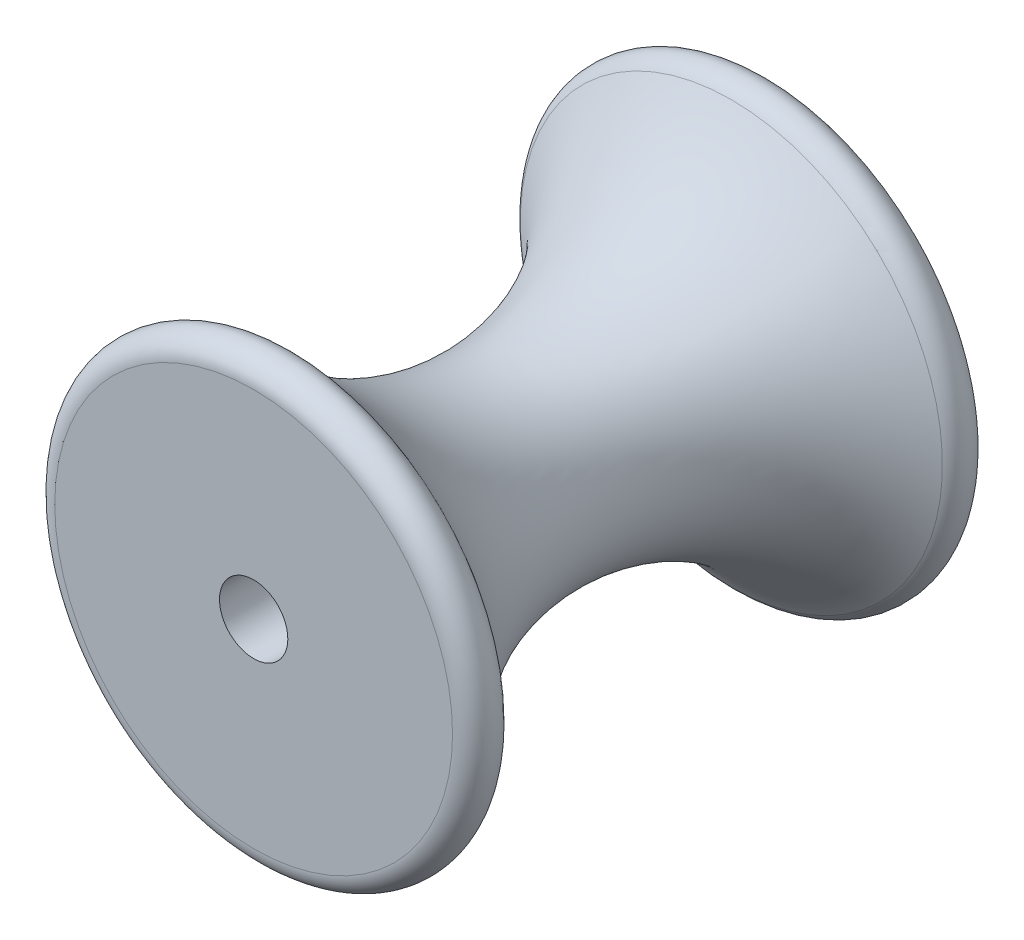
SolidWorks part; units mm, degrees
ref_plane "Front Plane" through (0, 0, 0) normal (0, 0, 1) x (1, 0, 0)
ref_plane "Top Plane" through (0, 0, 0) normal (0, 1, 0) x (1, 0, 0)
ref_plane "Right Plane" through (0, 0, 0) normal (1, 0, 0) x (0, 0, -1)
sketch "Sketch1" plane through (0, 0, 0) normal (1, 0, 0) x (0, 0, -1)
  line L0 (12.5, 0) -> (-12.5, 0) construction
  line L1 (8.0683, 13.3135) -> (18.8033, -18.936) construction
  line L2 (12.5, 1.6) -> (-12.5, 1.6) construction
  line L3 (-12.5, -23.7788) -> (-12.5, -25.7788) construction
  line L4 (0, 55) -> (0, -55) construction
  line L5 (12.5, 1.6) -> (12.5, 17) construction
  line L6 (-12.5, 1.6) -> (-12.5, 17) construction
  line L7 (12.1, 1.6) -> (12.1, 13.8631)
  line L8 (-12.1, 1.6) -> (-12.1, 13.8631)
  line L9 (12.1, 1.6) -> (-12.1, 1.6)
  circle A0 centre (0, 17) radius 12.5 construction
  arc A1 (12.1, 13.8631) -> (-12.1, 13.8631) centre (0, 17) cw
  point P2 (0, 0)
  dimension "D1" = 0.8
revolve "Revolve1" add sketch "Sketch1" angle 360 about L0
fillet "Fillet1" radius 1 2 edges at (0, 13.8631, 12.1) (0, 13.8631, -12.1)
